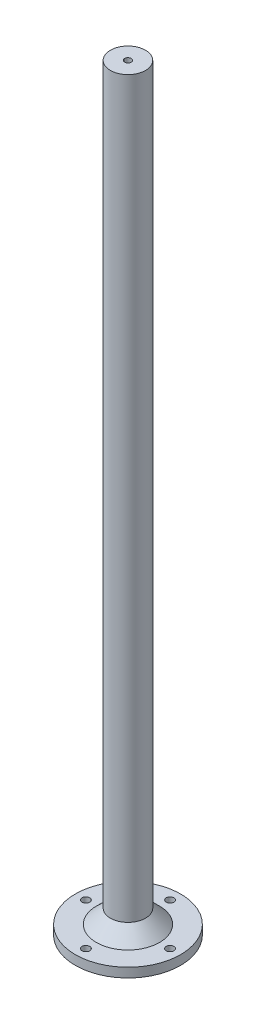
SolidWorks part; units mm, degrees
ref_plane "前视基准面" through (0, 0, 0) normal (0, 0, 1) x (1, 0, 0)
ref_plane "上视基准面" through (0, 0, 0) normal (0, 1, 0) x (1, 0, 0)
ref_plane "右视基准面" through (0, 0, 0) normal (1, 0, 0) x (0, 0, -1)
other "Configuration Table"
sketch "草图1" plane through (0, 0, 0) normal (0, 1, 0) x (1, 0, 0)
  line L0 (0, 0) -> (-18, 0) construction
  line L1 (0, 0) -> (18, 0) construction
  line L2 (0, 0) -> (0, 18) construction
  line L3 (0, 0) -> (0, -18) construction
  circle A0 centre (0, 0) radius 22.5
  circle A1 centre (-18, 0) radius 1.65
  circle A2 centre (18, 0) radius 1.65
  circle A3 centre (0, 18) radius 1.65
  circle A7 centre (0, -18) radius 1.65
  point P12 (-96.7164, 69.864)
  point P13 (0, 0)
  point P14 (0, 0)
  point P15 (0, 0)
  dimension "D1" = 45
  dimension "D2" = 3.3
  dimension "D3" = 18
  dimension "D4" = 18
extrude "凸台-拉伸1" add sketch "草图1" along normal blind 4
sketch "草图2" plane through (0, 4, 0) normal (0, 1, 0) x (1, 0, 0)
  circle A0 centre (0, 0) radius 7.5
  dimension "D1" = 15
extrude "凸台-拉伸2" add sketch "草图2" along normal blind 320
sketch "草图3" plane through (0, 324, 0) normal (0, 1, 0) x (1, 0, 0)
  circle A0 centre (0, 0) radius 1.4
  dimension "D1" = 2.8
extrude "切除-拉伸1" cut sketch "草图3" against normal blind 10
chamfer "倒角1" distance 6 angle 45 1 edges at (0, 4, 7.5)
